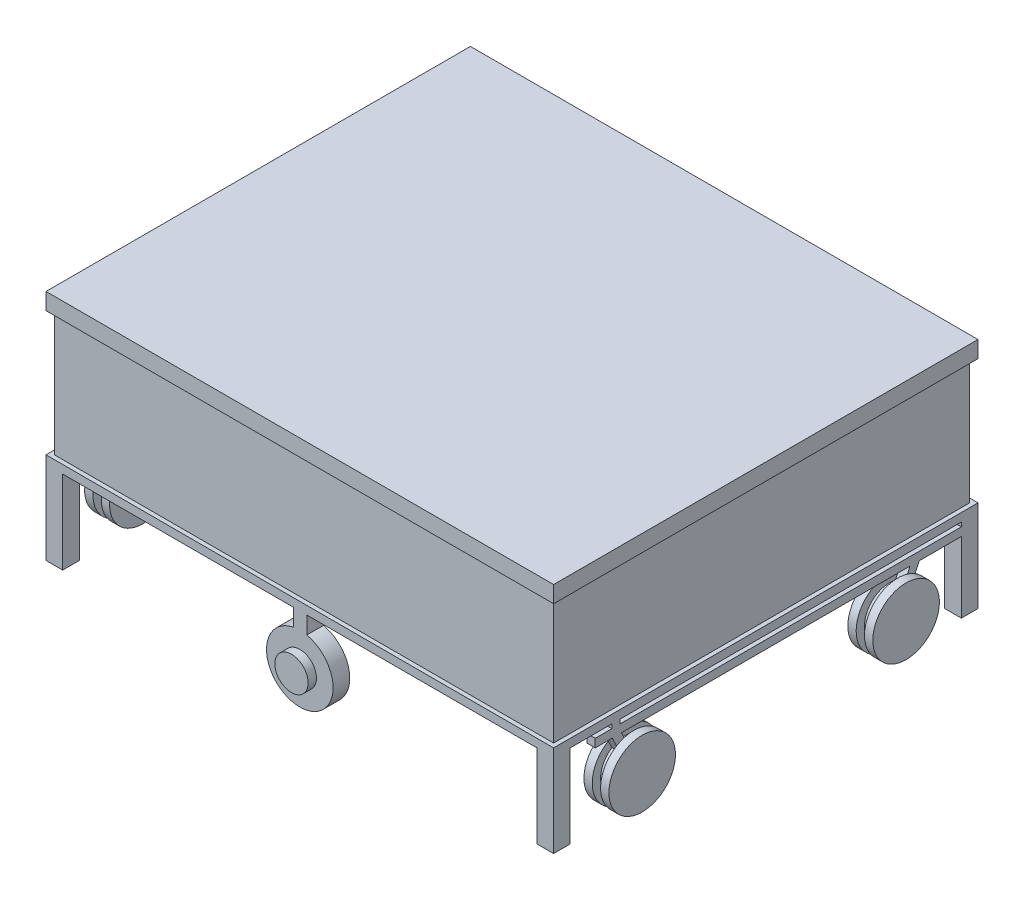
SolidWorks part; units mm, degrees
ref_plane "Ön Düzlem" through (0, 0, 0) normal (0, 0, 1) x (1, 0, 0)
ref_plane "Üst Düzlem" through (0, 0, 0) normal (0, 1, 0) x (1, 0, 0)
ref_plane "Sağ Düzlem" through (0, 0, 0) normal (1, 0, 0) x (0, 0, -1)
sketch "Sketch2" plane through (0, 0, 0) normal (0, 0, 1) x (1, 0, 0)
  line L1 (0, 0) -> (610, 0)
  line L2 (0, 0) -> (0, -110)
  line L3 (0, -110) -> (610, -110)
  line L4 (610, 0) -> (610, -110)
  dimension "D1" = 610
  dimension "D2" = 110
extrude "Boss-Extrude1" add sketch "Sketch2" along normal blind 510
sketch "Sketch3" plane through (0, 0, 0) normal (0, 1, 0) x (1, 0, 0)
  line L0 (0, -510) -> (0, 0) construction
  line L1 (55, -20) -> (555, -20)
  line L2 (55, -20) -> (55, -490)
  line L3 (55, -490) -> (555, -490)
  line L4 (555, -20) -> (555, -490)
  line L5 (610, -510) -> (610, 0) construction
  line L6 (610, 0) -> (0, 0) construction
  line L7 (610, -510) -> (0, -510) construction
  dimension "D1" = 55
  dimension "D2" = 55
  dimension "D3" = 20
  dimension "D4" = 20
extrude "Cut-Extrude1" cut sketch "Sketch3" against normal blind 510
sketch "Sketch4" plane through (0, 0, 510) normal (0, 0, 1) x (1, 0, 0)
  line L0 (0, -110) -> (610, -110) construction
  line L1 (20, -10) -> (590, -10)
  line L2 (20, -10) -> (20, -110)
  line L3 (20, -110) -> (590, -110)
  line L4 (590, -10) -> (590, -110)
  line L5 (610, 0) -> (0, 0) construction
  line L6 (0, 0) -> (0, -110) construction
  line L7 (610, -110) -> (610, 0) construction
  dimension "D1" = 10
  dimension "D2" = 20
  dimension "D3" = 20
extrude "Cut-Extrude2" cut sketch "Sketch4" against normal blind 510
sketch "Sketch5" plane through (610, 0, 0) normal (1, 0, 0) x (0, 0, -1)
  line L0 (-510, -110) -> (0, -110) construction
  line L1 (-490, -10) -> (-20, -10)
  line L2 (-490, -10) -> (-490, -110)
  line L3 (-490, -110) -> (-20, -110)
  line L4 (-20, -10) -> (-20, -110)
  line L5 (-510, 0) -> (0, 0) construction
  line L6 (-510, -110) -> (-510, 0) construction
  line L7 (0, -110) -> (0, 0) construction
  dimension "D1" = 10
  dimension "D2" = 20
  dimension "D3" = 20
extrude "Cut-Extrude4" cut sketch "Sketch5" against normal blind 610
sketch "Sketch7" plane through (0, 0, 0) normal (0, 1, 0) x (1, 0, 0)
  line L0 (0, -510) -> (0, 0) construction
  line L1 (5, -5) -> (605, -5)
  line L2 (5, -5) -> (5, -505)
  line L3 (5, -505) -> (605, -505)
  line L4 (605, -5) -> (605, -505)
  line L5 (610, 0) -> (0, 0) construction
  dimension "D1" = 600
  dimension "D2" = 500
  dimension "D3" = 5
  dimension "D4" = 5
extrude "Boss-Extrude2" add sketch "Sketch7" along normal blind 100
sketch "Sketch8" plane through (0, 100, 0) normal (0, 1, 0) x (1, 0, 0)
  line L0 (5, -5) -> (5, -505) construction
  line L1 (55, -55) -> (555, -55)
  line L2 (55, -55) -> (55, -455)
  line L3 (55, -455) -> (555, -455)
  line L4 (555, -55) -> (555, -455)
  line L5 (605, -505) -> (605, -5) construction
  line L6 (605, -5) -> (5, -5) construction
  line L7 (5, -505) -> (605, -505) construction
  dimension "D1" = 50
  dimension "D2" = 50
  dimension "D3" = 50
  dimension "D4" = 50
extrude "Boss-Extrude3" add sketch "Sketch8" along normal blind 20
sketch "Sketch9" plane through (0, 120, 0) normal (0, 1, 0) x (1, 0, 0)
  line L1 (5, -5) -> (605, -5)
  line L2 (5, -5) -> (5, -505)
  line L3 (5, -505) -> (605, -505)
  line L4 (605, -5) -> (605, -505)
extrude "Boss-Extrude4" add sketch "Sketch9" along normal blind 50
sketch "Sketch10" plane through (0, 0, 505) normal (0, 0, 1) x (1, 0, 0)
  circle A0 centre (5, 170) radius 30
  circle A1 centre (605, 170) radius 30
extrude "Cut-Extrude5" cut sketch "Sketch10" against normal blind 600
sketch "Sketch11" plane through (610, 0, 0) normal (1, 0, 0) x (0, 0, -1)
  line L0 (-20, -10) -> (-490, -10) construction
  line L1 (-440, -10) -> (-430, -10)
  line L2 (-440, -10) -> (-440, -25)
  line L3 (-440, -25) -> (-430, -25)
  line L4 (-430, -10) -> (-430, -25)
  line L5 (-20, -110) -> (-20, -10) construction
  line L6 (-460, -25) -> (-20, -25)
  line L7 (-460, -25) -> (-460, -15)
  line L8 (-460, -15) -> (-20, -15)
  line L9 (-20, -25) -> (-20, -15)
  line L10 (-510, -110) -> (-510, 0) construction
  line M4 (-20, -10) -> (-20, -110)
  dimension "D1" = 50
  dimension "D2" = 10
  dimension "D3" = 15
  dimension "D4" = 15
  dimension "D5" = 10
  dimension "D6" = 70
extrude "Boss-Extrude5" add sketch "Sketch11" against normal blind 10 contours L8 L4 L6 M4 | L8 L2 L3 L4 | L8 L7 L6 L2
sketch "Sketch12" plane through (610, 0, 0) normal (1, 0, 0) x (0, 0, -1)
  line L0 (-439.6109, -25) -> (-424.2078, -56.4284)
  line L1 (-439.6109, -25) -> (-430.6313, -20.5991)
  line L2 (-424.2078, -56.4284) -> (-415.2282, -52.0275)
  line L3 (-430.6313, -20.5991) -> (-415.2282, -52.0275)
  line L4 (-460, -25) -> (-20, -25) construction
  line L5 (-505, 0) -> (-5, 0) construction
  line L6 (-255, 170) -> (-255, -154.3538) construction
  line L7 (-5, 170) -> (-505, 170) construction
  line L8 (-79.3687, -20.5991) -> (-94.7718, -52.0275)
  line L9 (-85.7922, -56.4284) -> (-94.7718, -52.0275)
  line L10 (-70.3891, -25) -> (-79.3687, -20.5991)
  line L11 (-70.3891, -25) -> (-85.7922, -56.4284)
  circle A0 centre (-413.5773, -70) radius 30
  circle A1 centre (-96.4227, -70) radius 30
  line M11 (-460, -25) -> (-20, -25)
  dimension "D3" = 70
  dimension "D1" = 35
  dimension "D2" = 10
extrude "Boss-Extrude11" add sketch "Sketch12" against normal blind 10 contours L0 A0 L3 L2 | A1 L8 L9 L11 | L8 A1 L11 M11 | A1 L11 L9 L8 | A0 L3 L0 M11 | L3 A0 L0 L2
sketch "Sketch17" plane through (610, 0, 0) normal (1, 0, 0) x (0, 0, -1)
  line L1 (-255, 170) -> (-255, -145.6765) construction
  line L2 (-5, 170) -> (-505, 170) construction
  line L3 (-255, 170) -> (-255, -154.3538) construction
  circle A0 centre (-413.5773, -70) radius 40
  circle A1 centre (-96.4227, -70) radius 40
extrude "Boss-Extrude12" add sketch "Sketch17" along normal blind 10
sketch "Sketch18" plane through (600, 0, 0) normal (-1, 0, 0) x (0, 0, 1)
  line L1 (255, 170) -> (255, -148.7619) construction
  line L2 (505, 170) -> (5, 170) construction
  line L3 (255, 170) -> (255, -154.3538) construction
  circle A0 centre (96.4227, -70) radius 40
  circle A1 centre (413.5773, -70) radius 40
extrude "Boss-Extrude13" add sketch "Sketch18" along normal blind 10
sketch "Sketch19" plane through (0, 0, 0) normal (-1, 0, 0) x (0, 0, 1)
  line L1 (20, -15) -> (460, -15)
  line L2 (20, -15) -> (20, -25)
  line L3 (20, -25) -> (460, -25)
  line L4 (460, -15) -> (460, -25)
  line L5 (430, -10) -> (439.6109, -10)
  line L6 (430, -10) -> (430, -25)
  line L7 (430, -25) -> (439.6109, -25)
  line L8 (439.6109, -10) -> (439.6109, -25)
extrude "Boss-Extrude14" add sketch "Sketch19" against normal blind 10 contours L3 L4 L1 L2 | L5 L8 L7 L6
sketch "Sketch20" plane through (0, 0, 0) normal (-1, 0, 0) x (0, 0, 1)
  line L0 (70.3891, -25) -> (85.7922, -56.4284)
  line L1 (70.3891, -25) -> (79.385, -20.5911)
  line L2 (85.7922, -56.4284) -> (94.7881, -52.0195)
  line L3 (79.385, -20.5911) -> (94.7881, -52.0195)
  line L4 (255, 170) -> (255, -154.3538) construction
  line L5 (424.2078, -56.4284) -> (415.2119, -52.0195)
  line L6 (430.615, -20.5911) -> (415.2119, -52.0195)
  line L7 (439.6109, -25) -> (430.615, -20.5911)
  line L8 (439.6109, -25) -> (424.2078, -56.4284)
  circle A0 centre (96.4227, -70) radius 30
  circle A1 centre (413.5773, -70) radius 30
  line M10 (20, -25) -> (460, -25)
extrude "Boss-Extrude15" add sketch "Sketch20" against normal blind 10 contours L0 A0 L3 L2 | A0 L3 L0 M10 | A1 L8 L5 L6 | L6 A1 L8 M10
sketch "Sketch21" plane through (0, 0, 0) normal (-1, 0, 0) x (0, 0, 1)
  circle A0 centre (96.4227, -70) radius 40
  circle A1 centre (413.5773, -70) radius 40
extrude "Boss-Extrude16" add sketch "Sketch21" along normal blind 10
sketch "Sketch22" plane through (10, 0, 0) normal (1, 0, 0) x (0, 0, -1)
  circle A0 centre (-413.5773, -70) radius 40
  circle A1 centre (-96.4227, -70) radius 40
extrude "Boss-Extrude17" add sketch "Sketch22" along normal blind 10
sketch "Sketch23" plane through (5, 0, 0) normal (-1, 0, 0) x (0, 0, 1)
  line L0 (225, 130) -> (245, 130) construction
  line L1 (225, 135) -> (245, 135)
  line L2 (225, 125) -> (245, 125)
  line L4 (505, 140) -> (5, 140) construction
  line L5 (5, 120) -> (505, 120) construction
  line L6 (255, 170) -> (255, 77.5022) construction
  line L7 (255, 170) -> (255, -154.3538) construction
  line L8 (285, 130) -> (265, 130) construction
  line L9 (285, 135) -> (265, 135)
  line L10 (285, 125) -> (265, 125)
  arc A0 (225, 135) -> (225, 125) centre (225, 130) ccw
  arc A1 (245, 125) -> (245, 135) centre (245, 130) ccw
  arc A2 (285, 135) -> (285, 125) centre (285, 130) cw
  arc A3 (265, 125) -> (265, 135) centre (265, 130) cw
  point P2 (235, 130)
  point P20 (275, 130)
  dimension "D1" = 10
  dimension "D2" = 5
  dimension "D3" = 5
  dimension "D4" = 20
extrude "Cut-Extrude7" cut sketch "Sketch23" against normal blind 610
sketch "Sketch24" plane through (0, 0, 510) normal (0, 0, 1) x (1, 0, 0)
  line L0 (-10, -70) -> (305, -70) construction
  line L1 (-10, -30) -> (-10, -110) construction
  line L2 (590, -10) -> (20, -10) construction
  line L3 (297.3688, -10) -> (313.3688, -10)
  line L4 (297.3688, -10) -> (297.3688, -70)
  line L5 (297.3688, -70) -> (313.3688, -70)
  line L6 (313.3688, -10) -> (313.3688, -70)
  line L7 (305.3688, 11.9567) -> (305.3688, -145.1185) construction
  circle A0 centre (305, -70) radius 40
  dimension "D1" = 16
  dimension "D2" = 8
extrude "Boss-Extrude18" add sketch "Sketch24" against normal blind 20 contours L4 A0 L6 L5
sketch "Sketch25" plane through (0, 0, 510) normal (0, 0, 1) x (1, 0, 0)
  circle A0 centre (305, -70) radius 20
extrude "Cut-Extrude8" cut sketch "Sketch25" against normal blind 20
sketch "Sketch26" plane through (0, 0, 0) normal (0, 0, -1) x (-1, 0, 0)
  line L1 (-313.3688, -10) -> (-297.3688, -10)
  line L2 (-313.3688, -10) -> (-313.3688, -70)
  line L3 (-313.3688, -70) -> (-297.3688, -70)
  line L4 (-297.3688, -10) -> (-297.3688, -70)
  circle A0 centre (-305, -70) radius 40
  circle A1 centre (-305, -70) radius 20
  line M1 (-590, -10) -> (-20, -10)
  dimension "D1" = 16
extrude "Boss-Extrude19" add sketch "Sketch26" against normal blind 20 contours A1 L2 A0 L4 | A0 L4 L2 M1 | A1 L4 A0 L2
sketch "Sketch27" plane through (0, 0, 0) normal (0, 0, -1) x (-1, 0, 0)
  circle A0 centre (-305, -70) radius 20
extrude "Boss-Extrude20" add sketch "Sketch27" along normal blind 10 separate body
sketch "Sketch28" plane through (0, 0, 20) normal (0, 0, 1) x (1, 0, 0)
  circle A0 centre (305, -70) radius 20
extrude "Boss-Extrude21" add sketch "Sketch28" along normal blind 10 separate body
sketch "Sketch29" plane through (0, 0, 510) normal (0, 0, 1) x (1, 0, 0)
  circle A0 centre (305, -70) radius 20
extrude "Boss-Extrude22" add sketch "Sketch29" along normal blind 10 separate body
sketch "Sketch30" plane through (0, 0, 490) normal (0, 0, -1) x (-1, 0, 0)
  circle A0 centre (-305, -70) radius 20
extrude "Boss-Extrude23" add sketch "Sketch30" along normal blind 10 separate body
sketch "Sketch31" plane through (0, 100, 0) normal (0, 1, 0) x (1, 0, 0)
  line L1 (5, -5) -> (605, -5)
  line L2 (5, -5) -> (5, -505)
  line L3 (5, -505) -> (605, -505)
  line L4 (605, -5) -> (605, -505)
extrude "Boss-Extrude24" add sketch "Sketch31" along normal blind 70
sketch "Sketch32" plane through (0, 170, 0) normal (0, 1, 0) x (1, 0, 0)
  line L1 (0, 0) -> (610, 0)
  line L2 (0, 0) -> (0, -510)
  line L3 (0, -510) -> (610, -510)
  line L4 (610, 0) -> (610, -510)
extrude "Boss-Extrude25" add sketch "Sketch32" against normal blind 20
